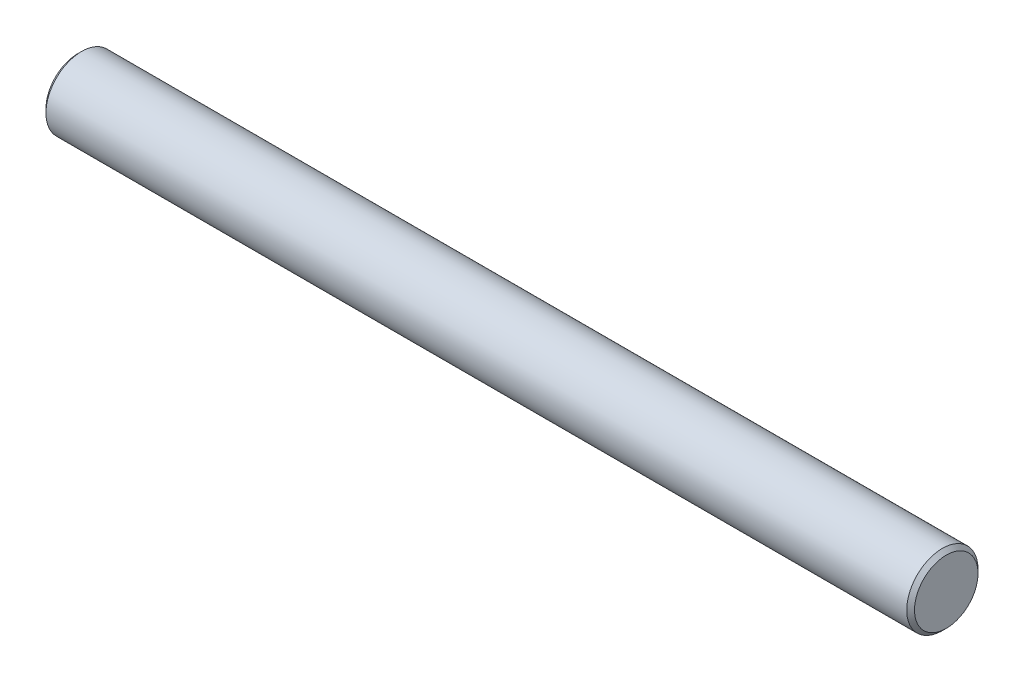
SolidWorks part; units mm, degrees
ref_plane "Front Plane" through (0, 0, 0) normal (0, 0, 1) x (1, 0, 0)
ref_plane "Top Plane" through (0, 0, 0) normal (0, 1, 0) x (1, 0, 0)
ref_plane "Right Plane" through (0, 0, 0) normal (1, 0, 0) x (0, 0, -1)
sketch "Sketch1" plane through (0, 0, 0) normal (0, 0, 1) x (1, 0, 0)
  line L0 (-33.5, 2.45) -> (-33.5, 0)
  line L1 (-33.5, 0) -> (33.5, 0)
  line L2 (33.5, 0) -> (33.5, 2.45)
  line L3 (33.5, 2.45) -> (33.2, 2.75)
  line L4 (33.2, 2.75) -> (-33.2, 2.75)
  line L5 (-33.2, 2.75) -> (-33.5, 2.45)
  line L6 (-33.5, 0) -> (33.5, 0) construction
revolve "Revolve1" add sketch "Sketch1" angle 360 about L6
scale "Scale1" scale about centroid uniform scaling yes scale factor 0.3333
